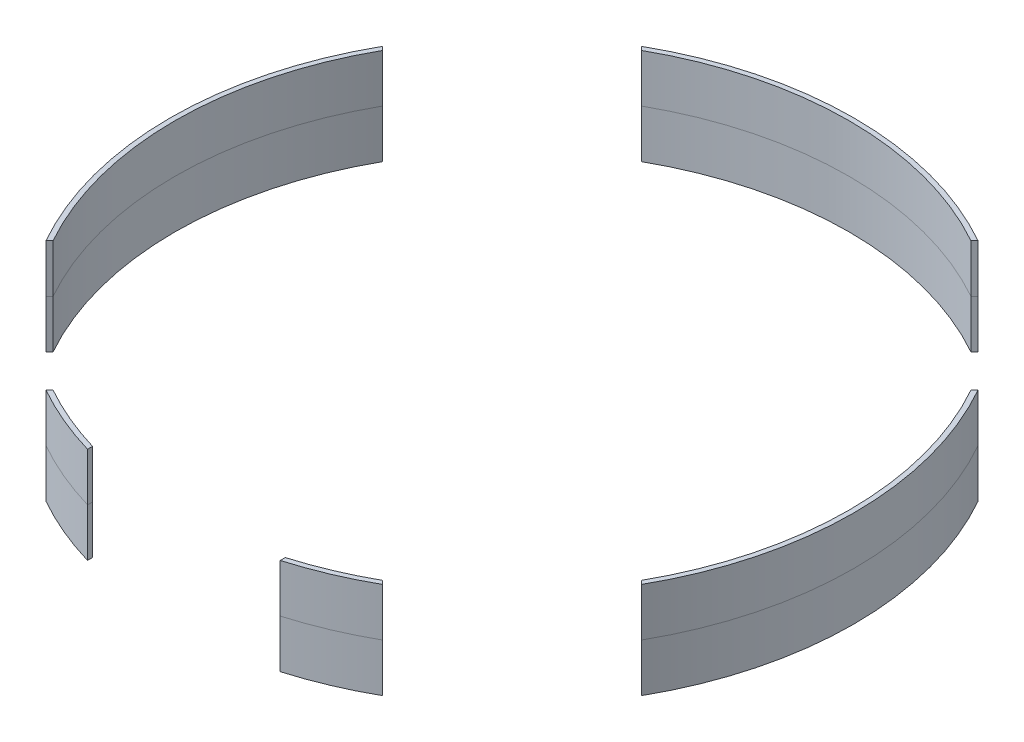
SolidWorks part; units mm, degrees
ref_plane "Front Plane" through (0, 0, 0) normal (0, 0, 1) x (1, 0, 0)
ref_plane "Top Plane" through (0, 0, 0) normal (0, 1, 0) x (1, 0, 0)
ref_plane "Right Plane" through (0, 0, 0) normal (1, 0, 0) x (0, 0, -1)
sketch "Sketch1" plane through (0, 0, 0) normal (0, 1, 0) x (1, 0, 0)
  circle A0 centre (0, 0) radius 140
  circle A1 centre (0, 0) radius 142
  dimension "D1" = 2
  dimension "D2" = 280
extrude "Boss-Extrude1" add sketch "Sketch1" along normal blind 20
sketch "Sketch2" plane through (0, 20, 0) normal (0, 1, 0) x (1, 0, 0)
  circle A0 centre (0, 0) radius 140
  circle A1 centre (0, 0) radius 142
  circle A2 centre (0, 0) radius 140 construction
  circle A3 centre (0, 0) radius 142 construction
extrude "Boss-Extrude2" add sketch "Sketch2" along normal blind 20 separate body
sketch "Sketch3" plane through (0, 40, 0) normal (0, 1, 0) x (1, 0, 0)
  line L1 (-40, -134.1641) -> (40, -134.1641)
  line L2 (-40, -134.1641) -> (-40, -142)
  line L3 (-40, -142) -> (40, -142)
  line L4 (40, -134.1641) -> (40, -142)
  circle A0 centre (0, 0) radius 140 construction
  circle A1 centre (0, 0) radius 142 construction
  dimension "D1" = 80
extrude "Cut-Extrude1" cut sketch "Sketch3" against normal through all
sketch "Sketch4" plane through (0, 40, 0) normal (0, 1, 0) x (1, 0, 0)
  line L0 (-125.6797, 125.6797) -> (125.6797, -125.6797) construction
  line L1 (0, 0) -> (0, 71.485) construction
  line L2 (-127.2792, 73.5391) -> (-73.5391, 127.2792)
  line L3 (-127.2792, 73.5391) -> (-122.1486, 68.4085)
  line L4 (-73.5391, 127.2792) -> (-68.4085, 122.1486)
  line L5 (-122.1486, 68.4085) -> (-68.4085, 122.1486)
  line L6 (68.4085, -122.1486) -> (122.1486, -68.4085)
  line L7 (68.4085, -122.1486) -> (73.5391, -127.2792)
  line L8 (122.1486, -68.4085) -> (127.2792, -73.5391)
  line L9 (73.5391, -127.2792) -> (127.2792, -73.5391)
  line L10 (134.2295, 134.2295) -> (-134.2295, -134.2295) construction
  line L11 (73.5391, 127.2792) -> (127.2792, 73.5391)
  line L12 (73.5391, 127.2792) -> (68.4085, 122.1486)
  line L13 (127.2792, 73.5391) -> (122.1486, 68.4085)
  line L14 (68.4085, 122.1486) -> (122.1486, 68.4085)
  line L15 (-127.2792, -73.5391) -> (-73.5391, -127.2792)
  line L16 (-127.2792, -73.5391) -> (-122.1486, -68.4085)
  line L17 (-73.5391, -127.2792) -> (-68.4085, -122.1486)
  line L18 (-122.1486, -68.4085) -> (-68.4085, -122.1486)
  arc A0 (40, -136.2498) -> (-40, -136.2498) centre (0, 0) ccw construction
  arc A1 (40, -134.1641) -> (-40, -134.1641) centre (0, 0) ccw construction
  dimension "D1" = 45
  dimension "D2" = 76
extrude "Cut-Extrude2" cut sketch "Sketch4" against normal through all
